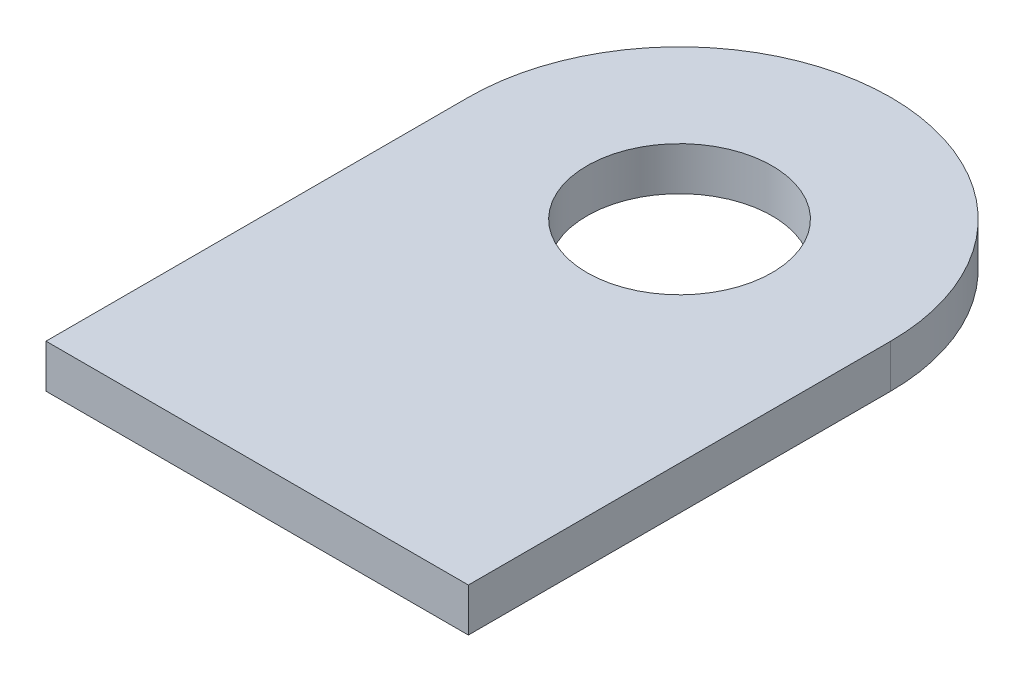
SolidWorks part; units mm, degrees
ref_plane "Front Plane" through (0, 0, 0) normal (0, 0, 1) x (1, 0, 0)
ref_plane "Top Plane" through (0, 0, 0) normal (0, 1, 0) x (1, 0, 0)
ref_plane "Right Plane" through (0, 0, 0) normal (1, 0, 0) x (0, 0, -1)
sketch "Sketch1" plane through (0, 0, 0) normal (0, 1, 0) x (1, 0, 0)
  line L1 (0, 0) -> (15, 0)
  line L2 (0, 0) -> (0, 15)
  line L4 (15, 0) -> (15, 15)
  arc A0 (0, 15) -> (15, 15) centre (7.5, 15) cw
  circle A1 centre (7.5, 15) radius 3.288
  dimension "D3" = 15
  dimension "D4" = 6.5761
  dimension "D1" = 15
extrude "Boss-Extrude1" add sketch "Sketch1" along normal blind 1.54 contours A1 | L1 L4 A0 L2
sketch "Sketch2" plane through (0, 0, 0) normal (1, 0, 0) x (0, 0, -1)
  line L3 (0, 1.54) -> (15, 1.54) construction
  circle A0 centre (0, 14.24) radius 12.7
  point P2 (-8.9139, 13.7751)
  point P5 (0, 14.24)
  point P6 (0, 0)
  dimension "D1" = 25.4
